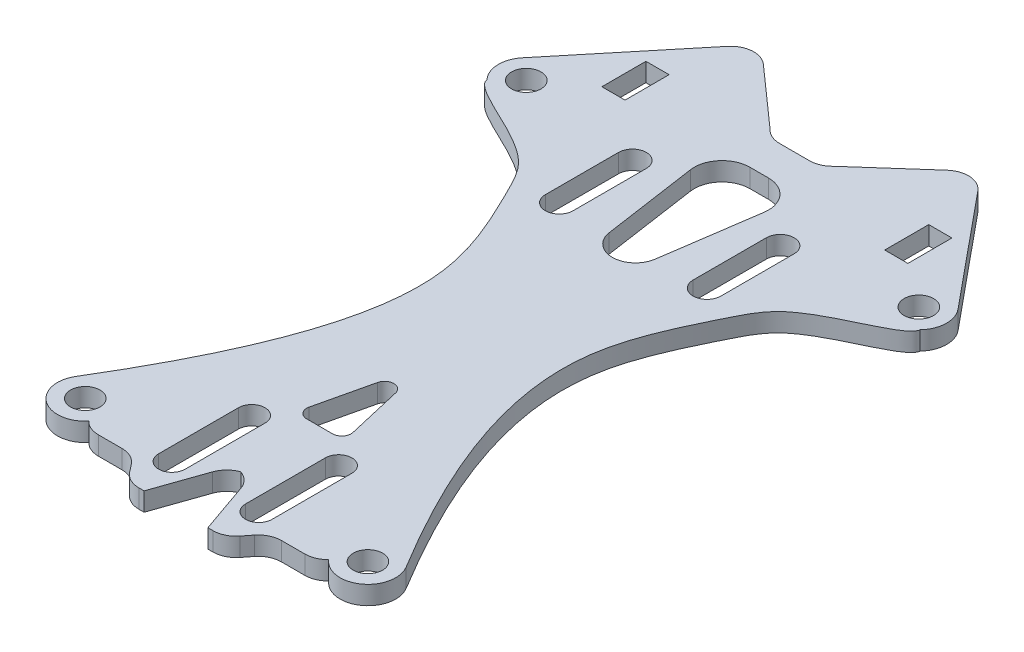
SolidWorks part; units mm, degrees
ref_plane "Alzado" through (0, 0, 0) normal (0, 0, 1) x (1, 0, 0)
ref_plane "Planta" through (0, 0, 0) normal (0, 1, 0) x (1, 0, 0)
ref_plane "Vista lateral" through (0, 0, 0) normal (1, 0, 0) x (0, 0, -1)
sketch "Croquis1" plane through (0, 0, 0) normal (0, 1, 0) x (1, 0, 0)
  line L0 (0, 0) -> (0, -2.5005) construction
  line L2 (-3.6329, -113.0793) -> (172.3671, -113.0793) construction
  line L3 (-23.4827, 26.1265) -> (-13.501, 38.2475)
  line L6 (-1.6089, 31.9861) -> (0.564, 31.9861)
  line L8 (14, 32.4531) -> (14, 27.7031)
  line L9 (-16.5, 32.4531) -> (-14, 32.4531)
  line L10 (-16.5, 32.4531) -> (-16.5, 27.7031)
  line L11 (-16.5, 27.7031) -> (-14, 27.7031)
  line L12 (-14, 32.4531) -> (-14, 27.7031)
  line L13 (-11.1387, -31.9483) -> (-8.5987, -31.9483)
  line L14 (-6.6341, -32.9023) -> (-5.9532, -33.7675)
  line L15 (-3.9886, -34.7215) -> (-3.4412, -34.7215)
  line L16 (-3.4412, -34.7215) -> (-1.5339, -29.2621)
  line L17 (-4.6848, -21.8677) -> (-4.6848, -30.476) construction
  line L18 (-3.2497, -21.8677) -> (-3.2497, -30.476)
  line L19 (3.4412, -34.7215) -> (1.5339, -29.2621)
  line L20 (3.9886, -34.7215) -> (3.4412, -34.7215)
  line L21 (6.6341, -32.9023) -> (5.9532, -33.7675)
  line L22 (11.1387, -31.9483) -> (8.5987, -31.9483)
  line L27 (-11.1387, -31.9483) -> (-8.5987, -31.9483)
  line L28 (1.6089, 31.9861) -> (-0.564, 31.9861)
  line L29 (3.4412, 32.7853) -> (9.9117, 38.528)
  line L30 (-3.4412, 32.7853) -> (-9.9117, 38.528)
  line L31 (16.5, 27.7031) -> (14, 27.7031)
  line L32 (0.564, 31.9861) -> (-0.564, 31.9861)
  line L33 (-6.1198, -21.8677) -> (-6.1198, -30.476)
  line L34 (-7.969, 22.4708) -> (-7.969, 14.5718) construction
  line L35 (-6.4697, 22.4708) -> (-6.4697, 14.5718)
  line L36 (-9.4684, 22.4708) -> (-9.4684, 14.5718)
  line L37 (4.6848, -21.8677) -> (4.6848, -30.476) construction
  line L38 (3.2497, -21.8677) -> (3.2497, -30.476)
  line L39 (6.1198, -21.8677) -> (6.1198, -30.476)
  line L40 (7.969, 22.4708) -> (7.969, 14.5718) construction
  line L41 (6.4697, 22.4708) -> (6.4697, 14.5718)
  line L42 (9.4684, 22.4708) -> (9.4684, 14.5718)
  line L43 (-0.9741, -12.0051) -> (-2.3679, -18.0051)
  line L44 (-1.3938, -19.2314) -> (0.7639, -19.2314)
  line L45 (1.3938, -19.2314) -> (-0.7639, -19.2314)
  line L46 (0.9741, -12.0051) -> (2.3679, -18.0051)
  line L47 (-1.0018, 28.1672) -> (1.0018, 28.1672)
  line L48 (3.9704, 24.7344) -> (2.4738, 14.4687)
  line L49 (-3.9704, 24.7344) -> (-2.4738, 14.4687)
  line L54 (16.5, 32.4531) -> (16.5, 27.7031)
  line L55 (16.5, 32.4531) -> (14, 32.4531)
  line L56 (23.4827, 26.1265) -> (13.501, 38.2475)
  circle A8 centre (-21.1669, 24.2194) radius 1.59
  arc A9 (-3.4412, 32.7853) -> (-1.6089, 31.9861) centre (-1.6089, 34.4861) ccw
  arc A10 (0, -27.7272) -> (-1.5339, -29.2621) centre (0.8263, -30.0867) ccw
  arc A11 (-3.9886, -34.7215) -> (-5.9532, -33.7675) centre (-3.9886, -32.2215) cw
  arc A12 (-6.6341, -32.9023) -> (-8.5987, -31.9483) centre (-8.5987, -34.4483) ccw
  circle A13 centre (-15.2379, -29.2621) radius 1.5875
  arc A14 (11.1387, -31.9483) -> (12.936, -31.186) centre (11.1387, -29.4483) ccw
  arc A15 (6.6341, -32.9023) -> (8.5987, -31.9483) centre (8.5987, -34.4483) cw
  arc A16 (3.9886, -34.7215) -> (5.9532, -33.7675) centre (3.9886, -32.2215) ccw
  arc A17 (0, -27.7272) -> (1.5339, -29.2621) centre (-0.8263, -30.0867) cw
  arc A18 (3.4412, 32.7853) -> (1.6089, 31.9861) centre (1.6089, 34.4861) cw
  arc A19 (-23.4827, 26.1265) -> (-23.3584, 22.1706) centre (-21.1669, 24.2194) ccw
  arc A24 (-3.2497, -21.8677) -> (-6.1198, -21.8677) centre (-4.6848, -21.8677) ccw
  arc A25 (-6.1198, -30.476) -> (-3.2497, -30.476) centre (-4.6848, -30.476) ccw
  arc A26 (-6.4697, 22.4708) -> (-9.4684, 22.4708) centre (-7.969, 22.4708) ccw
  arc A27 (-9.4684, 14.5718) -> (-6.4697, 14.5718) centre (-7.969, 14.5718) ccw
  arc A28 (3.2497, -21.8677) -> (6.1198, -21.8677) centre (4.6848, -21.8677) cw
  arc A29 (6.1198, -30.476) -> (3.2497, -30.476) centre (4.6848, -30.476) cw
  arc A30 (6.4697, 22.4708) -> (9.4684, 22.4708) centre (7.969, 22.4708) cw
  arc A31 (9.4684, 14.5718) -> (6.4697, 14.5718) centre (7.969, 14.5718) cw
  arc A32 (0.9741, -12.0051) -> (-0.9741, -12.0051) centre (0, -12.2314) ccw
  arc A33 (1.3938, -19.2314) -> (2.3679, -18.0051) centre (1.3938, -18.2314) ccw
  arc A34 (-2.3679, -18.0051) -> (-1.3938, -19.2314) centre (-1.3938, -18.2314) ccw
  arc A35 (1.0018, 28.1672) -> (3.9704, 24.7344) centre (1.0018, 25.1672) cw
  arc A36 (-1.0018, 28.1672) -> (-3.9704, 24.7344) centre (-1.0018, 25.1672) ccw
  arc A37 (2.4738, 14.4687) -> (-2.4738, 14.4687) centre (0, 14.8294) cw
  arc A38 (-9.9117, 38.528) -> (-13.501, 38.2475) centre (-11.5712, 36.6582) ccw
  arc A39 (-17.8154, -27.7272) -> (-12.936, -31.186) centre (-15.2379, -29.2621) ccw
  arc A40 (9.9117, 38.528) -> (13.501, 38.2475) centre (11.5712, 36.6582) cw
  circle A43 centre (15.2379, -29.2621) radius 1.5875
  arc A44 (16.8049, -26.7039) -> (12.936, -31.186) centre (15.2379, -29.2621) cw
  arc A45 (-11.1387, -31.9483) -> (-12.936, -31.186) centre (-11.1387, -29.4483) cw
  arc A46 (23.4827, 26.1265) -> (23.3584, 22.1706) centre (21.1669, 24.2194) cw
  circle A47 centre (21.1669, 24.2194) radius 1.59
  arc A48 (-15.25, 13.175) -> (-15.25, 17.325) centre (-15.25, 15.25) ccw construction
  circle A49 centre (-15.2379, -29.2621) radius 3 construction
  arc A50 (2.2193, 27.0276) -> (-2.2193, 27.0276) centre (0, 25.8767) ccw construction
  spline S0 degree 3 poles (-17.8154, -27.7272) (-10.4947, -15.6524) (-5.5893, -1.2532) (-9.5754, 8.4978) (-14.6815, 18.4103) (-23.1362, 20.5405) (-23.3584, 22.1706) knots 0 0 0 0 0.481002 0.786245 0.838145 1 1 1 1
  spline S1 degree 3 poles (16.8049, -26.7039) (8.8709, -16.5331) (5.6973, -8.8601) (6.4697, 0) knots 0.022248 0.022248 0.022248 0.022248 0.449041 0.449041 0.449041 0.449041
  spline S2 degree 3 poles (17.8154, -27.7272) (10.4947, -15.6524) (5.5893, -1.2532) (9.5754, 8.4978) (14.6815, 18.4103) (23.1362, 20.5405) (23.3584, 22.1706) knots 0 0 0 0 0.481002 0.786245 0.838145 1 1 1 1
  point P15 (-4.6848, -26.1719)
  point P52 (-7.969, 18.5213)
  point P92 (4.6848, -26.1719)
  point P99 (7.969, 18.5213)
  point P111 (0, -7.812)
  point P114 (2.6528, -19.2314)
  point P117 (-2.6528, -19.2314)
  point P123 (4.4709, 28.1672)
  point P126 (-4.4709, 28.1672)
extrude "Saliente-Extruir2" add sketch "Croquis1" along normal blind 2 contours A44 S2 S1 A46 L56 A40 L29 A18 L28 L32 L6 A9 L30 A38 L3 A19 S0 A39 A45 L13 A12 L14 A11 L15 L16 A10 A17 L19 L20 A16 L21 A15 L22 A14 A47 L48 A37 L49 A36 L47 A35 L42 A31 L41 A30 L39
